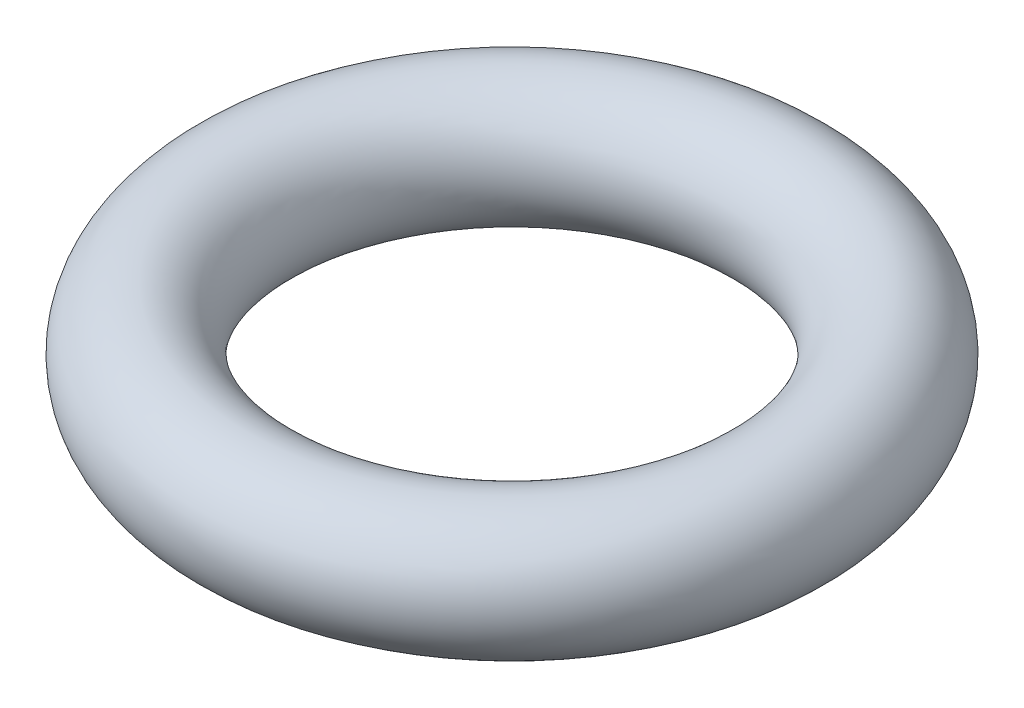
SolidWorks part; units mm, degrees
ref_plane "Front Plane" through (0, 0, 0) normal (0, 0, 1) x (1, 0, 0)
ref_plane "Top Plane" through (0, 0, 0) normal (0, 1, 0) x (1, 0, 0)
ref_plane "Right Plane" through (0, 0, 0) normal (1, 0, 0) x (0, 0, -1)
sketch "Sketch1" plane through (0, 0, 0) normal (1, 0, 0) x (0, 0, -1)
  line L0 (0, 0) -> (1.5878, 0) construction
  line L1 (1.5878, 0) -> (2.0878, 0) construction
  line L2 (0, 0) -> (0, 0.8717) construction
  circle A0 centre (2.0878, 0) radius 0.5
revolve "Revolve1" add sketch "Sketch1" angle 360 about L2
